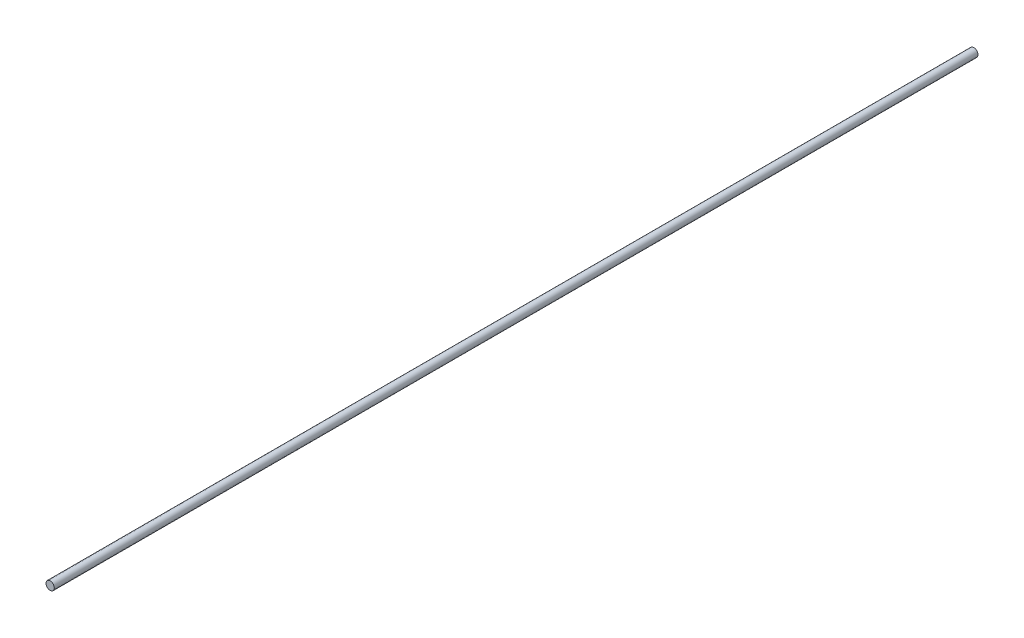
SolidWorks part; units mm, degrees
ref_plane "Plan de face" through (0, 0, 0) normal (0, 0, 1) x (1, 0, 0)
ref_plane "Plan de dessus" through (0, 0, 0) normal (0, 1, 0) x (1, 0, 0)
ref_plane "Plan de droite" through (0, 0, 0) normal (1, 0, 0) x (0, 0, -1)
sketch "Esquisse1" plane through (0, 0, 0) normal (0, 0, 1) x (1, 0, 0)
  circle A0 centre (0, 0) radius 0.9
  dimension "D1" = 1.8
extrude "Boss.-Extru.1" add sketch "Esquisse1" along normal blind 200
cosmetic thread "Représentation de filetage1" parameters "D1"=10, "D2"=1.202
cosmetic thread "Représentation de filetage2" parameters "D1"=10, "D2"=1.202
